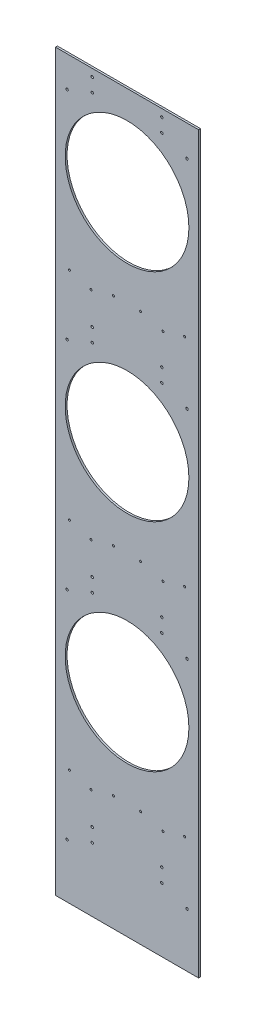
SolidWorks part; units mm, degrees
material "PC High Viscosity"
ref_plane "Front Plane" through (0, 0, 0) normal (0, 0, 1) x (1, 0, 0)
ref_plane "Top Plane" through (0, 0, 0) normal (0, 1, 0) x (1, 0, 0)
ref_plane "Right Plane" through (0, 0, 0) normal (1, 0, 0) x (0, 0, -1)
sketch "Sketch1" plane through (0, 0, 0) normal (0, 0, 1) x (1, 0, 0)
  line L0 (0, 695.96) -> (0, 1407.16) construction
  line L1 (-234.95, 0) -> (234.95, 0)
  line L2 (-234.95, 0) -> (-234.95, 2413)
  line L3 (-234.95, 2413) -> (234.95, 2413)
  line L4 (234.95, 0) -> (234.95, 2413)
  circle A0 centre (0, 695.96) radius 203.2
  circle A1 centre (0, 1407.16) radius 203.2
  circle A2 centre (0, 2118.36) radius 203.2
  dimension "D3" = 406.4
  dimension "D1" = 2413
  dimension "D2" = 469.9
  dimension "D4" = 492.76
  dimension "D6" = 711.2
  dimension "D5" = 3
extrude "Boss-Extrude1" add sketch "Sketch1" along normal blind 6.35
hole_wizard "1/4 Clearance Hole1" positions "Sketch2" profile "Sketch3" hole size "1/4" standard "ANSI Inch"
sketch "Sketch2" plane through (0, 0, 6.35) normal (0, 0, 1) x (1, 0, 0)
  line L0 (0, 0) -> (0, 2413) construction
  line L1 (234.95, 2413) -> (-234.95, 2413) construction
  line L3 (2.839, 370.0053) -> (12.7, 406.807) construction
  line L4 (2.839, 370.0053) -> (225.089, 310.4536) construction
  line L5 (12.7, 406.807) -> (234.95, 347.2553) construction
  line L6 (225.089, 310.4536) -> (234.95, 347.2553) construction
  line L7 (234.95, 0) -> (234.95, 2413) construction
  line L8 (-234.95, 0) -> (234.95, 0) construction
  line L9 (7.7695, 388.4062) -> (230.0195, 328.8545) construction
  line L11 (118.1748, 358.8231) -> (118.1748, 1070.0231) construction
  line L12 (12.7, 406.807) -> (0, 410.21) construction
  line L14 (12.7, 406.807) -> (14.3435, 412.9407) construction
  line L15 (12.7, 406.807) -> (233.3065, 347.6957) construction
  line L16 (14.3435, 412.9407) -> (234.95, 353.8293) construction
  line L17 (233.3065, 347.6957) -> (234.95, 353.8293) construction
  circle A0 centre (189.3721, 379.1899) radius 6.35 construction
  point P0 (44.5713, 378.5452)
  point P2 (118.1748, 358.8231)
  point P4 (-44.5713, 378.5452)
  point P6 (-118.1748, 358.8231)
  point P187 (44.5713, 1089.7452)
  point P188 (118.1748, 1070.0231)
  point P189 (-44.5713, 1089.7452)
  point P190 (-118.1748, 1070.0231)
  point P191 (44.5713, 1800.9452)
  point P192 (118.1748, 1781.2231)
  point P193 (-44.5713, 1800.9452)
  point P194 (-118.1748, 1781.2231)
  point P380 (189.3721, 379.1899)
  point P382 (-189.3721, 379.1899)
  point P386 (-189.3721, 1090.3899)
  point P387 (-189.3721, 1801.5899)
  point P388 (189.3721, 1801.5899)
  point P389 (189.3721, 1090.3899)
  point P453 (114.3, 968.375) [skipped]
  point P454 (114.3, 923.925) [skipped]
  dimension "D10" = 12.7
  dimension "D11" = 6.35
  dimension "D1" = 38.1
  dimension "D2" = 410.21
  dimension "D3" = 15
  dimension "D4" = 38.1
  dimension "D5" = 114.3
  dimension "D7" = 711.2
  dimension "D8" = 12.7
  dimension "D9" = 6.35
  dimension "D12" = 177.8
  dimension "D6" = 3
sketch "Sketch3" plane through (44.5713, 378.5452, 6.35) normal (1, 0, 0) x (0, -1, 0)
  line L0 (0, 0) -> (0, 6.35)
  line L1 (0, 6.35) -> (3.3782, 6.35)
  line L2 (3.3782, 6.35) -> (3.3782, 0)
  line L5 (3.3782, 0) -> (0, 0)
  line L11 (0, -6.35) -> (0, 107.95) construction
  dimension "Thru Hole Dia." = 6.7564
  dimension "Thru Hole Depth" = 6.35
hole_wizard "5/16 (0.3125) Diameter Hole1" positions "Sketch4" profile "Sketch5" hole size "5/16" standard "ANSI Inch" end condition through all
sketch "Sketch4" plane through (0, 0, 6.35) normal (0, 0, 1) x (1, 0, 0)
  line L0 (0, 0) -> (0, 2413) construction
  line L1 (234.95, 2413) -> (-234.95, 2413) construction
  line L3 (0, 232.41) -> (-114.3, 232.41) construction
  line L5 (-114.3, 254.635) -> (-114.3, 210.185) construction
  line L7 (-234.95, 2413) -> (-234.95, 0) construction
  line L8 (-234.95, 0) -> (234.95, 0) construction
  point P0 (-114.3, 254.635)
  point P2 (-114.3, 210.185)
  point P4 (-196.85, 177.8)
  point P27 (196.85, 177.8)
  point P28 (114.3, 210.185)
  point P29 (114.3, 254.635)
  point P41 (-114.3, 965.835)
  point P42 (-114.3, 921.385)
  point P43 (-196.85, 889)
  point P44 (196.85, 889)
  point P45 (114.3, 921.385)
  point P46 (114.3, 965.835)
  point P47 (-114.3, 1677.035)
  point P48 (-114.3, 1632.585)
  point P49 (-196.85, 1600.2)
  point P50 (196.85, 1600.2)
  point P51 (114.3, 1632.585)
  point P52 (114.3, 1677.035)
  point P53 (-114.3, 2388.235)
  point P54 (-114.3, 2343.785)
  point P55 (-196.85, 2311.4)
  point P56 (196.85, 2311.4)
  point P57 (114.3, 2343.785)
  point P58 (114.3, 2388.235)
  dimension "D1" = 114.3
  dimension "D2" = 44.45
  dimension "D3" = 38.1
  dimension "D4" = 177.8
  dimension "D5" = 232.41
  dimension "D7" = 711.2
  dimension "D6" = 4
sketch "Sketch5" plane through (-114.3, 254.635, 6.35) normal (1, 0, 0) x (0, -1, 0)
  line L0 (0, 0) -> (0, 6.35)
  line L1 (0, 6.35) -> (3.9687, 6.35)
  line L2 (3.9687, 6.35) -> (3.9687, 0)
  line L5 (3.9687, 0) -> (0, 0)
  line L11 (0, -6.35) -> (0, 107.95) construction
  dimension "Thru Hole Dia." = 7.9375
  dimension "Thru Hole Depth" = 6.35
